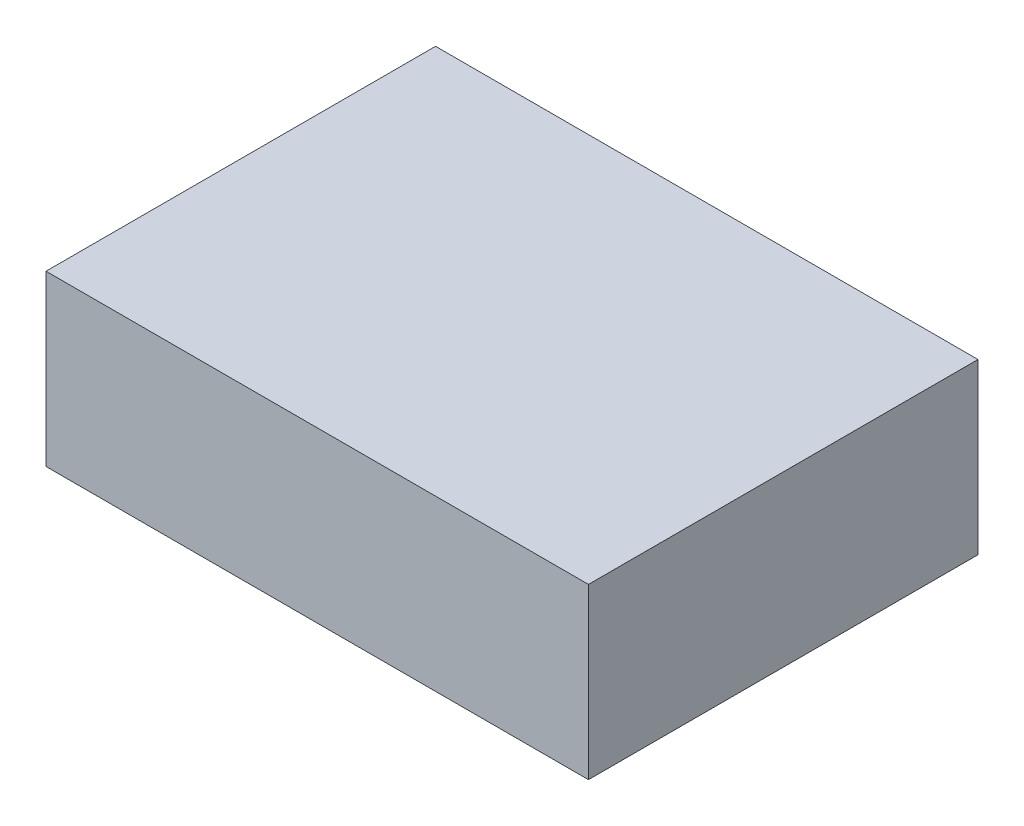
SolidWorks part; units mm, degrees
material "AISI 1010 Steel, hot rolled bar"
ref_plane "Front Plane" through (0, 0, 0) normal (0, 0, 1) x (1, 0, 0)
ref_plane "Top Plane" through (0, 0, 0) normal (0, 1, 0) x (1, 0, 0)
ref_plane "Right Plane" through (0, 0, 0) normal (1, 0, 0) x (0, 0, -1)
other "Configuration Table"
sketch "Sketch1" plane through (0, 0, 0) normal (0, 1, 0) x (1, 0, 0)
  line L5 (-57.7292, 46.6023) -> (88.0993, 46.6023)
  line L6 (-57.7292, 46.6023) -> (-57.7292, -58.122)
  line L7 (-57.7292, -58.122) -> (88.0993, -58.122)
  line L8 (88.0993, 46.6023) -> (88.0993, -58.122)
extrude "Boss-Extrude1" add sketch "Sketch1" along normal blind 45.466
